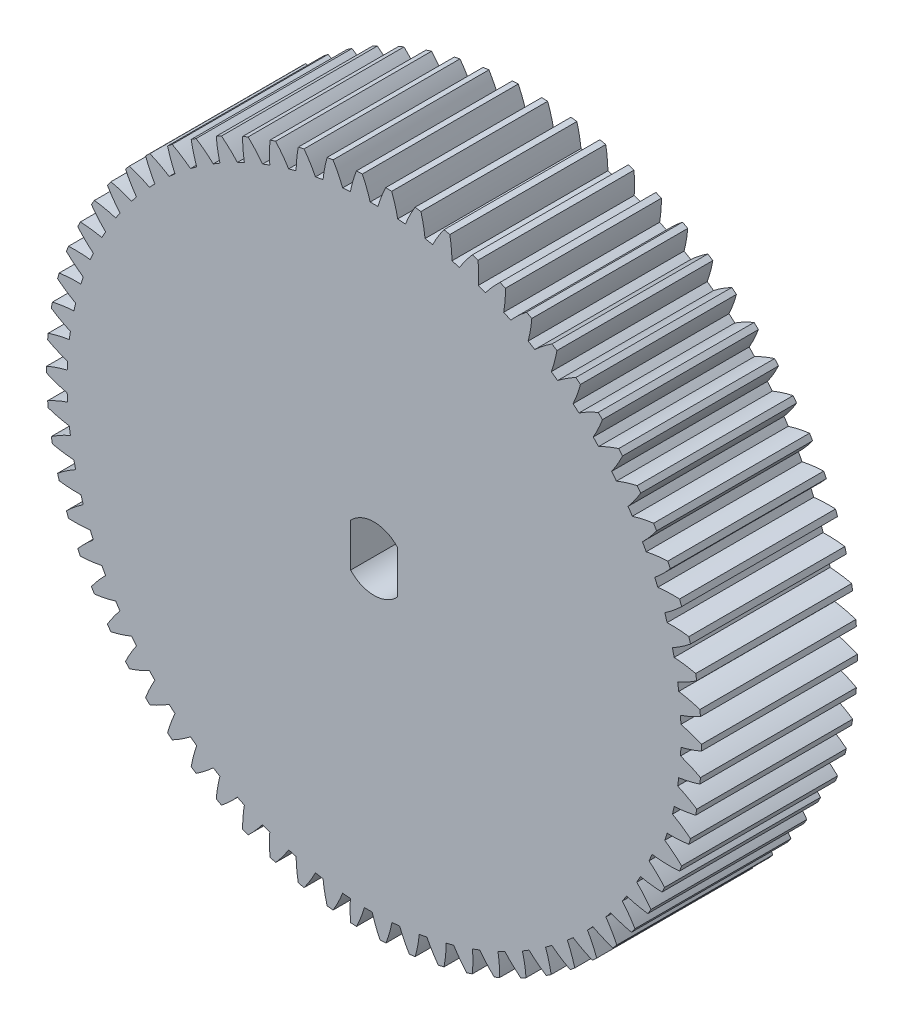
SolidWorks part; units mm, degrees
material "ABS"
ref_plane "Alzado" through (0, 0, 0) normal (0, 0, 1) x (1, 0, 0)
ref_plane "Planta" through (0, 0, 0) normal (0, 1, 0) x (1, 0, 0)
ref_plane "Vista lateral" through (0, 0, 0) normal (1, 0, 0) x (0, 0, -1)
sketch "Croquis1" plane through (0, 0, 0) normal (0, 0, 1) x (1, 0, 0)
  line L0 (0, 0) -> (0, 2.45) construction
  line L1 (0, 0) -> (0, 2.45) construction
  line L2 (-1.8, 1.6621) -> (-1.8, -1.6621)
  line L3 (1.8, 1.6621) -> (1.8, -1.6621)
  arc A0 (-25.199, -0.2281) -> (-23.6117, -0.7622) centre (-21.2911, 8.7591) ccw
  arc A1 (-23.6117, -0.7622) -> (-23.585, -1.3574) centre (0, 0) ccw
  arc A2 (-23.585, -1.3574) -> (-25.118, -2.0316) centre (-20.4203, -10.6323) ccw
  arc A3 (-25.118, -2.0316) -> (-25.0771, -2.486) centre (0, 0) ccw
  arc A4 (-25.0771, -2.486) -> (-23.4483, -2.8757) centre (-21.9906, 6.8153) ccw
  arc A5 (-23.4483, -2.8757) -> (-23.3684, -3.4661) centre (0, 0) ccw
  arc A6 (-23.3684, -3.4661) -> (-24.8347, -4.275) centre (-19.385, -12.42) ccw
  arc A7 (-24.8347, -4.275) -> (-24.7533, -4.7239) centre (0, 0) ccw
  arc A8 (-24.7533, -4.7239) -> (-23.0961, -4.966) centre (-22.513, 4.8166) ccw
  arc A9 (-23.0961, -4.966) -> (-22.9636, -5.5468) centre (0, 0) ccw
  arc A10 (-22.9636, -5.5468) -> (-24.3515, -6.484) centre (-18.1936, -14.1076) ccw
  arc A11 (-24.3515, -6.484) -> (-24.2302, -6.9237) centre (0, 0) ccw
  arc A12 (-24.2302, -6.9237) -> (-22.558, -7.0163) centre (-22.8541, 2.7792) ccw
  arc A13 (-22.558, -7.0163) -> (-22.3739, -7.5829) centre (0, 0) ccw
  arc A14 (-22.3739, -7.5829) -> (-23.6723, -8.6407) centre (-16.8558, -15.6817) ccw
  arc A15 (-23.6723, -8.6407) -> (-23.512, -9.0678) centre (0, 0) ccw
  arc A16 (-23.512, -9.0678) -> (-21.8383, -9.0102) centre (-23.0112, 0.7194) ccw
  arc A17 (-21.8383, -9.0102) -> (-21.6041, -9.558) centre (0, 0) ccw
  arc A18 (-21.6041, -9.558) -> (-22.8024, -10.7279) centre (-15.3822, -17.1295) ccw
  arc A19 (-22.8024, -10.7279) -> (-22.6045, -11.1389) centre (0, 0) ccw
  arc A20 (-22.6045, -11.1389) -> (-20.9427, -10.9315) centre (-22.9831, -1.3462) ccw
  arc A21 (-20.9427, -10.9315) -> (-20.6604, -11.4561) centre (0, 0) ccw
  arc A22 (-20.6604, -11.4561) -> (-21.749, -12.7287) centre (-13.7848, -18.4394) ccw
  arc A23 (-21.749, -12.7287) -> (-21.515, -13.1203) centre (0, 0) ccw
  arc A24 (-21.515, -13.1203) -> (-19.8785, -12.7648) centre (-22.7699, -3.401) ccw
  arc A25 (-19.8785, -12.7648) -> (-19.5503, -13.262) centre (0, 0) ccw
  arc A26 (-19.5503, -13.262) -> (-20.5205, -14.6271) centre (-12.0764, -19.6009) ccw
  arc A27 (-20.5205, -14.6271) -> (-20.2523, -14.9961) centre (0, 0) ccw
  arc A28 (-20.2523, -14.9961) -> (-18.6542, -14.4953) centre (-22.3733, -5.4284) ccw
  arc A29 (-18.6542, -14.4953) -> (-18.2828, -14.961) centre (0, 0) ccw
  arc A30 (-18.2828, -14.961) -> (-19.1267, -16.4076) centre (-10.2708, -20.6045) ccw
  arc A31 (-19.1267, -16.4076) -> (-18.8266, -16.7511) centre (0, 0) ccw
  arc A32 (-18.8266, -16.7511) -> (-17.2798, -16.1091) centre (-21.7967, -7.4121) ccw
  arc A33 (-17.2798, -16.1091) -> (-16.8681, -16.5397) centre (0, 0) ccw
  arc A34 (-16.8681, -16.5397) -> (-17.5789, -18.0561) centre (-8.3825, -21.4422) ccw
  arc A35 (-17.5789, -18.0561) -> (-17.2492, -18.3713) centre (0, 0) ccw
  arc A36 (-17.2492, -18.3713) -> (-15.7662, -17.5932) centre (-21.0445, -9.3361) ccw
  arc A37 (-15.7662, -17.5932) -> (-15.3176, -17.9851) centre (0, 0) ccw
  arc A38 (-15.3176, -17.9851) -> (-15.8896, -19.5591) centre (-6.4267, -22.1073) ccw
  arc A39 (-15.8896, -19.5591) -> (-15.533, -19.8436) centre (0, 0) ccw
  arc A40 (-15.533, -19.8436) -> (-14.1257, -18.9356) centre (-20.1229, -11.1849) ccw
  arc A41 (-14.1257, -18.9356) -> (-13.6437, -19.2858) centre (0, 0) ccw
  arc A42 (-13.6437, -19.2858) -> (-14.0724, -20.9047) centre (-4.4191, -22.5944) ccw
  arc A43 (-14.0724, -20.9047) -> (-13.6917, -21.156) centre (0, 0) ccw
  arc A44 (-13.6917, -21.156) -> (-12.3715, -20.1256) centre (-19.0393, -12.9437) ccw
  arc A45 (-12.3715, -20.1256) -> (-11.8601, -20.4312) centre (0, 0) ccw
  arc A46 (-11.8601, -20.4312) -> (-12.1419, -22.082) centre (-2.376, -22.8995) ccw
  arc A47 (-12.1419, -22.082) -> (-11.7401, -22.2982) centre (0, 0) ccw
  arc A48 (-11.7401, -22.2982) -> (-10.5176, -21.1536) centre (-17.8024, -14.5982) ccw
  arc A49 (-10.5176, -21.1536) -> (-9.9809, -21.412) centre (0, 0) ccw
  arc A50 (-9.9809, -21.412) -> (-10.1136, -23.0815) centre (-0.3137, -23.0203) ccw
  arc A51 (-10.1136, -23.0815) -> (-9.6941, -23.2608) centre (0, 0) ccw
  arc A52 (-9.6941, -23.2608) -> (-8.5791, -22.0112) centre (-16.4222, -16.1353) ccw
  arc A53 (-8.5791, -22.0112) -> (-8.0213, -22.2205) centre (0, 0) ccw
  arc A54 (-8.0213, -22.2205) -> (-8.0038, -23.8952) centre (1.751, -22.9558) ccw
  arc A55 (-8.0038, -23.8952) -> (-7.57, -24.0361) centre (0, 0) ccw
  arc A56 (-7.57, -24.0361) -> (-6.5715, -22.6916) centre (-14.9097, -17.5424) ccw
  arc A57 (-6.5715, -22.6916) -> (-5.9972, -22.8501) centre (0, 0) ccw
  arc A58 (-5.9972, -22.8501) -> (-5.8297, -24.5164) centre (3.8017, -22.7064) ccw
  arc A59 (-5.8297, -24.5164) -> (-5.3849, -24.6179) centre (0, 0) ccw
  arc A60 (-5.3849, -24.6179) -> (-4.511, -23.1893) centre (-13.2772, -18.8083) ccw
  arc A61 (-4.511, -23.1893) -> (-3.9248, -23.2957) centre (0, 0) ccw
  arc A62 (-3.9248, -23.2957) -> (-3.6086, -24.9403) centre (5.8218, -22.2742) ccw
  arc A63 (-3.6086, -24.9403) -> (-3.1565, -25.0015) centre (0, 0) ccw
  arc A64 (-3.1565, -25.0015) -> (-2.4141, -23.5003) centre (-11.5378, -19.9227) ccw
  arc A65 (-2.4141, -23.5003) -> (-1.8208, -23.5537) centre (0, 0) ccw
  arc A66 (-1.8208, -23.5537) -> (-1.8, -25.1634) centre (7.9557, -24.2324) ccw
  arc A67 (-1.8, -25.1634) -> (-1.3443, -25.1838) centre (-0.4416, 0) ccw
  arc A68 (-1.3443, -25.1838) -> (-0.7395, -23.6221) centre (-10.1471, -20.8767) ccw
  arc A69 (-0.7395, -23.6221) -> (-0.1437, -23.6221) centre (-0.4416, 0) ccw
  arc A70 (-0.1437, -23.6221) -> (0.4611, -25.1838) centre (9.2639, -20.8767) ccw
  arc A71 (0.4611, -25.1838) -> (0.9168, -25.1634) centre (-0.4416, 0) ccw
  arc A72 (0.9168, -25.1634) -> (1.3792, -23.5537) centre (-8.2366, -21.6627) ccw
  arc A73 (1.3792, -23.5537) -> (1.9726, -23.5003) centre (-0.4416, 0) ccw
  arc A74 (1.9726, -23.5003) -> (2.7149, -25.0015) centre (11.0962, -19.9227) ccw
  arc A75 (2.7149, -25.0015) -> (3.167, -24.9403) centre (-0.4416, 0) ccw
  arc A76 (3.167, -24.9403) -> (3.4832, -23.2957) centre (-6.2634, -22.2742) ccw
  arc A77 (3.4832, -23.2957) -> (4.0694, -23.1893) centre (-0.4416, 0) ccw
  arc A78 (4.0694, -23.1893) -> (4.9433, -24.6179) centre (12.8356, -18.8083) ccw
  arc A79 (4.9433, -24.6179) -> (5.3881, -24.5164) centre (-0.4416, 0) ccw
  arc A80 (5.3881, -24.5164) -> (5.5556, -22.8501) centre (-4.2433, -22.7064) ccw
  arc A81 (5.5556, -22.8501) -> (6.1299, -22.6916) centre (-0.4416, 0) ccw
  arc A82 (6.1299, -22.6916) -> (7.1284, -24.0361) centre (14.4681, -17.5424) ccw
  arc A83 (7.1284, -24.0361) -> (7.5622, -23.8952) centre (-0.4416, 0) ccw
  arc A84 (7.5622, -23.8952) -> (7.5797, -22.2205) centre (-2.1926, -22.9558) ccw
  arc A85 (7.5797, -22.2205) -> (8.1375, -22.0112) centre (-0.4416, 0) ccw
  arc A86 (8.1375, -22.0112) -> (9.2525, -23.2608) centre (15.9806, -16.1353) ccw
  arc A87 (9.2525, -23.2608) -> (9.672, -23.0815) centre (-0.4416, 0) ccw
  arc A88 (9.672, -23.0815) -> (9.5393, -21.412) centre (-0.1278, -23.0203) ccw
  arc A89 (9.5393, -21.412) -> (10.076, -21.1536) centre (-0.4416, 0) ccw
  arc A90 (10.076, -21.1536) -> (11.2986, -22.2982) centre (17.3608, -14.5982) ccw
  arc A91 (11.2986, -22.2982) -> (11.7003, -22.082) centre (-0.4416, 0) ccw
  arc A92 (11.7003, -22.082) -> (11.4185, -20.4312) centre (1.9344, -22.8995) ccw
  arc A93 (11.4185, -20.4312) -> (11.9299, -20.1256) centre (-0.4416, 0) ccw
  arc A94 (11.9299, -20.1256) -> (13.2501, -21.156) centre (18.5977, -12.9437) ccw
  arc A95 (13.2501, -21.156) -> (13.6308, -20.9047) centre (-0.4416, 0) ccw
  arc A96 (13.6308, -20.9047) -> (13.2022, -19.2858) centre (3.9775, -22.5944) ccw
  arc A97 (13.2022, -19.2858) -> (13.6841, -18.9356) centre (-0.4416, 0) ccw
  arc A98 (13.6841, -18.9356) -> (15.0914, -19.8436) centre (19.6813, -11.1849) ccw
  arc A99 (15.0914, -19.8436) -> (15.448, -19.5591) centre (-0.4416, 0) ccw
  arc A100 (15.448, -19.5591) -> (14.876, -17.9851) centre (5.9851, -22.1073) ccw
  arc A101 (14.876, -17.9851) -> (15.3246, -17.5932) centre (-0.4416, 0) ccw
  arc A102 (15.3246, -17.5932) -> (16.8076, -18.3713) centre (20.6029, -9.3361) ccw
  arc A103 (16.8076, -18.3713) -> (17.1373, -18.0561) centre (-0.4416, 0) ccw
  arc A104 (17.1373, -18.0561) -> (16.4265, -16.5397) centre (7.9409, -21.4422) ccw
  arc A105 (16.4265, -16.5397) -> (16.8382, -16.1091) centre (-0.4416, 0) ccw
  arc A106 (16.8382, -16.1091) -> (18.385, -16.7511) centre (21.3551, -7.4121) ccw
  arc A107 (18.385, -16.7511) -> (18.6851, -16.4076) centre (-0.4416, 0) ccw
  arc A108 (18.6851, -16.4076) -> (17.8412, -14.961) centre (9.8292, -20.6045) ccw
  arc A109 (17.8412, -14.961) -> (18.2126, -14.4953) centre (-0.4416, 0) ccw
  arc A110 (18.2126, -14.4953) -> (19.8107, -14.9961) centre (21.9318, -5.4284) ccw
  arc A111 (19.8107, -14.9961) -> (20.0789, -14.6271) centre (-0.4416, 0) ccw
  arc A112 (20.0789, -14.6271) -> (19.1087, -13.262) centre (11.6349, -19.6009) ccw
  arc A113 (19.1087, -13.262) -> (19.4369, -12.7648) centre (-0.4416, 0) ccw
  arc A114 (19.4369, -12.7648) -> (21.0734, -13.1203) centre (22.3283, -3.401) ccw
  arc A115 (21.0734, -13.1203) -> (21.3074, -12.7287) centre (-0.4416, 0) ccw
  arc A116 (21.3074, -12.7287) -> (20.2188, -11.4561) centre (13.3432, -18.4394) ccw
  arc A117 (20.2188, -11.4561) -> (20.5011, -10.9315) centre (-0.4416, 0) ccw
  arc A118 (20.5011, -10.9315) -> (22.1629, -11.1389) centre (22.5415, -1.3462) ccw
  arc A119 (22.1629, -11.1389) -> (22.3609, -10.7279) centre (-0.4416, 0) ccw
  arc A120 (22.3609, -10.7279) -> (21.1625, -9.558) centre (14.9406, -17.1295) ccw
  arc A121 (21.1625, -9.558) -> (21.3967, -9.0102) centre (-0.4416, 0) ccw
  arc A122 (21.3967, -9.0102) -> (23.512, -9.0678) centre (22.7197, 0.7001) ccw
  arc A123 (23.512, -9.0678) -> (23.6723, -8.6407) centre (0, 0) ccw
  arc A124 (23.6723, -8.6407) -> (22.3739, -7.5829) centre (16.8558, -15.6817) ccw
  arc A125 (22.3739, -7.5829) -> (22.558, -7.0163) centre (0, 0) ccw
  arc A126 (22.558, -7.0163) -> (24.2302, -6.9237) centre (22.8541, 2.7792) ccw
  arc A127 (24.2302, -6.9237) -> (24.3515, -6.484) centre (0, 0) ccw
  arc A128 (24.3515, -6.484) -> (22.9636, -5.5468) centre (18.1936, -14.1076) ccw
  arc A129 (22.9636, -5.5468) -> (23.0961, -4.966) centre (0, 0) ccw
  arc A130 (23.0961, -4.966) -> (24.7533, -4.7239) centre (22.513, 4.8166) ccw
  arc A131 (24.7533, -4.7239) -> (24.8347, -4.275) centre (0, 0) ccw
  arc A132 (24.8347, -4.275) -> (23.3684, -3.4661) centre (19.385, -12.42) ccw
  arc A133 (23.3684, -3.4661) -> (23.4483, -2.8757) centre (0, 0) ccw
  arc A134 (23.4483, -2.8757) -> (25.0771, -2.486) centre (21.9906, 6.8153) ccw
  arc A135 (25.0771, -2.486) -> (25.118, -2.0316) centre (0, 0) ccw
  arc A136 (25.118, -2.0316) -> (23.585, -1.3574) centre (20.4203, -10.6323) ccw
  arc A137 (23.585, -1.3574) -> (23.6117, -0.7622) centre (0, 0) ccw
  arc A138 (23.6117, -0.7622) -> (25.199, -0.2281) centre (21.2911, 8.7591) ccw
  arc A139 (25.199, -0.2281) -> (25.199, 0.2281) centre (0, 0) ccw
  arc A140 (25.199, 0.2281) -> (23.6117, 0.7622) centre (21.2911, -8.7591) ccw
  arc A141 (23.6117, 0.7622) -> (23.585, 1.3574) centre (0, 0) ccw
  arc A142 (23.585, 1.3574) -> (25.118, 2.0316) centre (20.4203, 10.6323) ccw
  arc A143 (25.118, 2.0316) -> (25.0771, 2.486) centre (0, 0) ccw
  arc A144 (25.0771, 2.486) -> (23.4483, 2.8757) centre (21.9906, -6.8153) ccw
  arc A145 (23.4483, 2.8757) -> (23.3684, 3.4661) centre (0, 0) ccw
  arc A146 (23.3684, 3.4661) -> (24.8347, 4.275) centre (19.385, 12.42) ccw
  arc A147 (24.8347, 4.275) -> (24.7533, 4.7239) centre (0, 0) ccw
  arc A148 (24.7533, 4.7239) -> (23.0961, 4.966) centre (22.513, -4.8166) ccw
  arc A149 (23.0961, 4.966) -> (22.9636, 5.5468) centre (0, 0) ccw
  arc A150 (22.9636, 5.5468) -> (24.3515, 6.484) centre (18.1936, 14.1076) ccw
  arc A151 (24.3515, 6.484) -> (24.2302, 6.9237) centre (0, 0) ccw
  arc A152 (24.2302, 6.9237) -> (22.558, 7.0163) centre (22.8541, -2.7792) ccw
  arc A153 (22.558, 7.0163) -> (22.3739, 7.5829) centre (0, 0) ccw
  arc A154 (22.3739, 7.5829) -> (23.6723, 8.6407) centre (16.8558, 15.6817) ccw
  arc A155 (23.6723, 8.6407) -> (23.512, 9.0678) centre (0, 0) ccw
  arc A156 (23.512, 9.0678) -> (21.8383, 9.0102) centre (23.0112, -0.7194) ccw
  arc A157 (21.8383, 9.0102) -> (21.6041, 9.558) centre (0, 0) ccw
  arc A158 (21.6041, 9.558) -> (22.8024, 10.7279) centre (15.3822, 17.1295) ccw
  arc A159 (22.8024, 10.7279) -> (22.6045, 11.1389) centre (0, 0) ccw
  arc A160 (22.6045, 11.1389) -> (20.9427, 10.9315) centre (22.9831, 1.3462) ccw
  arc A161 (20.9427, 10.9315) -> (20.6604, 11.4561) centre (0, 0) ccw
  arc A162 (20.6604, 11.4561) -> (21.749, 12.7287) centre (13.7848, 18.4394) ccw
  arc A163 (21.749, 12.7287) -> (21.515, 13.1203) centre (0, 0) ccw
  arc A164 (21.515, 13.1203) -> (19.8785, 12.7648) centre (22.7699, 3.401) ccw
  arc A165 (19.8785, 12.7648) -> (19.5503, 13.262) centre (0, 0) ccw
  arc A166 (19.5503, 13.262) -> (20.5205, 14.6271) centre (12.0764, 19.6009) ccw
  arc A167 (20.5205, 14.6271) -> (20.2523, 14.9961) centre (0, 0) ccw
  arc A168 (20.2523, 14.9961) -> (18.6542, 14.4953) centre (22.3733, 5.4284) ccw
  arc A169 (18.6542, 14.4953) -> (18.2828, 14.961) centre (0, 0) ccw
  arc A170 (18.2828, 14.961) -> (19.1267, 16.4076) centre (10.2708, 20.6045) ccw
  arc A171 (19.1267, 16.4076) -> (18.8266, 16.7511) centre (0, 0) ccw
  arc A172 (18.8266, 16.7511) -> (17.2798, 16.1091) centre (21.7967, 7.4121) ccw
  arc A173 (17.2798, 16.1091) -> (16.8681, 16.5397) centre (0, 0) ccw
  arc A174 (16.8681, 16.5397) -> (17.5789, 18.0561) centre (8.3825, 21.4422) ccw
  arc A175 (17.5789, 18.0561) -> (17.2492, 18.3713) centre (0, 0) ccw
  arc A176 (17.2492, 18.3713) -> (15.7662, 17.5932) centre (21.0445, 9.3361) ccw
  arc A177 (15.7662, 17.5932) -> (15.3176, 17.9851) centre (0, 0) ccw
  arc A178 (15.3176, 17.9851) -> (15.8896, 19.5591) centre (6.4267, 22.1073) ccw
  arc A179 (15.8896, 19.5591) -> (15.533, 19.8436) centre (0, 0) ccw
  arc A180 (15.533, 19.8436) -> (14.1257, 18.9356) centre (20.1229, 11.1849) ccw
  arc A181 (14.1257, 18.9356) -> (13.6437, 19.2858) centre (0, 0) ccw
  arc A182 (13.6437, 19.2858) -> (14.0724, 20.9047) centre (4.4191, 22.5944) ccw
  arc A183 (14.0724, 20.9047) -> (13.6917, 21.156) centre (0, 0) ccw
  arc A184 (13.6917, 21.156) -> (12.3715, 20.1256) centre (19.0393, 12.9437) ccw
  arc A185 (12.3715, 20.1256) -> (11.8601, 20.4312) centre (0, 0) ccw
  arc A186 (11.8601, 20.4312) -> (12.1419, 22.082) centre (2.376, 22.8995) ccw
  arc A187 (12.1419, 22.082) -> (11.7401, 22.2982) centre (0, 0) ccw
  arc A188 (11.7401, 22.2982) -> (10.5176, 21.1536) centre (17.8024, 14.5982) ccw
  arc A189 (10.5176, 21.1536) -> (9.9809, 21.412) centre (0, 0) ccw
  arc A190 (9.9809, 21.412) -> (10.1136, 23.0815) centre (0.3137, 23.0203) ccw
  arc A191 (10.1136, 23.0815) -> (9.6941, 23.2608) centre (0, 0) ccw
  arc A192 (9.6941, 23.2608) -> (8.5791, 22.0112) centre (16.4222, 16.1353) ccw
  arc A193 (8.5791, 22.0112) -> (8.0213, 22.2205) centre (0, 0) ccw
  arc A194 (8.0213, 22.2205) -> (8.0038, 23.8952) centre (-1.751, 22.9558) ccw
  arc A195 (8.0038, 23.8952) -> (7.57, 24.0361) centre (0, 0) ccw
  arc A196 (7.57, 24.0361) -> (6.5715, 22.6916) centre (14.9097, 17.5424) ccw
  arc A197 (6.5715, 22.6916) -> (5.9972, 22.8501) centre (0, 0) ccw
  arc A198 (5.9972, 22.8501) -> (5.8297, 24.5164) centre (-3.8017, 22.7064) ccw
  arc A199 (5.8297, 24.5164) -> (5.3849, 24.6179) centre (0, 0) ccw
  arc A200 (5.3849, 24.6179) -> (4.511, 23.1893) centre (13.2772, 18.8083) ccw
  arc A201 (4.511, 23.1893) -> (3.9248, 23.2957) centre (0, 0) ccw
  arc A202 (3.9248, 23.2957) -> (3.6086, 24.9403) centre (-5.8218, 22.2742) ccw
  arc A203 (3.6086, 24.9403) -> (3.1565, 25.0015) centre (0, 0) ccw
  arc A204 (3.1565, 25.0015) -> (2.4141, 23.5003) centre (11.5378, 19.9227) ccw
  arc A205 (2.4141, 23.5003) -> (1.8208, 23.5537) centre (0, 0) ccw
  arc A206 (1.8208, 23.5537) -> (1.3584, 25.1634) centre (-7.795, 21.6627) ccw
  arc A207 (1.3584, 25.1634) -> (0.9027, 25.1838) centre (0, 0) ccw
  arc A208 (0.9027, 25.1838) -> (0.2979, 23.6221) centre (9.7055, 20.8767) ccw
  arc A209 (0.2979, 23.6221) -> (-0.2979, 23.6221) centre (0, 0) ccw
  arc A210 (-0.2979, 23.6221) -> (-0.9027, 25.1838) centre (-9.7055, 20.8767) ccw
  arc A211 (-0.9027, 25.1838) -> (-1.3584, 25.1634) centre (0, 0) ccw
  arc A212 (-1.3584, 25.1634) -> (-1.8208, 23.5537) centre (7.795, 21.6627) ccw
  arc A213 (-1.8208, 23.5537) -> (-2.4141, 23.5003) centre (0, 0) ccw
  arc A214 (-2.4141, 23.5003) -> (-3.1565, 25.0015) centre (-11.5378, 19.9227) ccw
  arc A215 (-3.1565, 25.0015) -> (-3.6086, 24.9403) centre (0, 0) ccw
  arc A216 (-3.6086, 24.9403) -> (-3.9248, 23.2957) centre (5.8218, 22.2742) ccw
  arc A217 (-3.9248, 23.2957) -> (-4.511, 23.1893) centre (0, 0) ccw
  arc A218 (-4.511, 23.1893) -> (-5.3849, 24.6179) centre (-13.2772, 18.8083) ccw
  arc A219 (-5.3849, 24.6179) -> (-5.8297, 24.5164) centre (0, 0) ccw
  arc A220 (-5.8297, 24.5164) -> (-5.9972, 22.8501) centre (3.8017, 22.7064) ccw
  arc A221 (-5.9972, 22.8501) -> (-6.5715, 22.6916) centre (0, 0) ccw
  arc A222 (-6.5715, 22.6916) -> (-7.57, 24.0361) centre (-14.9097, 17.5424) ccw
  arc A223 (-7.57, 24.0361) -> (-8.0038, 23.8952) centre (0, 0) ccw
  arc A224 (-8.0038, 23.8952) -> (-8.0213, 22.2205) centre (1.751, 22.9558) ccw
  arc A225 (-8.0213, 22.2205) -> (-8.5791, 22.0112) centre (0, 0) ccw
  arc A226 (-8.5791, 22.0112) -> (-9.6941, 23.2608) centre (-16.4222, 16.1353) ccw
  arc A227 (-9.6941, 23.2608) -> (-10.1136, 23.0815) centre (0, 0) ccw
  arc A228 (-10.1136, 23.0815) -> (-9.9809, 21.412) centre (-0.3137, 23.0203) ccw
  arc A229 (-9.9809, 21.412) -> (-10.5176, 21.1536) centre (0, 0) ccw
  arc A230 (-10.5176, 21.1536) -> (-11.7401, 22.2982) centre (-17.8024, 14.5982) ccw
  arc A231 (-11.7401, 22.2982) -> (-12.1419, 22.082) centre (0, 0) ccw
  arc A232 (-12.1419, 22.082) -> (-11.8601, 20.4312) centre (-2.376, 22.8995) ccw
  arc A233 (-11.8601, 20.4312) -> (-12.3715, 20.1256) centre (0, 0) ccw
  arc A234 (-12.3715, 20.1256) -> (-13.6917, 21.156) centre (-19.0393, 12.9437) ccw
  arc A235 (-13.6917, 21.156) -> (-14.0724, 20.9047) centre (0, 0) ccw
  arc A236 (-14.0724, 20.9047) -> (-13.6437, 19.2858) centre (-4.4191, 22.5944) ccw
  arc A237 (-13.6437, 19.2858) -> (-14.1257, 18.9356) centre (0, 0) ccw
  arc A238 (-14.1257, 18.9356) -> (-15.533, 19.8436) centre (-20.1229, 11.1849) ccw
  arc A239 (-15.533, 19.8436) -> (-15.8896, 19.5591) centre (0, 0) ccw
  arc A240 (-15.8896, 19.5591) -> (-15.3176, 17.9851) centre (-6.4267, 22.1073) ccw
  arc A241 (-15.3176, 17.9851) -> (-15.7662, 17.5932) centre (0, 0) ccw
  arc A242 (-15.7662, 17.5932) -> (-17.2492, 18.3713) centre (-21.0445, 9.3361) ccw
  arc A243 (-17.2492, 18.3713) -> (-17.5789, 18.0561) centre (0, 0) ccw
  arc A244 (-17.5789, 18.0561) -> (-16.8681, 16.5397) centre (-8.3825, 21.4422) ccw
  arc A245 (-16.8681, 16.5397) -> (-17.2798, 16.1091) centre (0, 0) ccw
  arc A246 (-17.2798, 16.1091) -> (-18.8266, 16.7511) centre (-21.7967, 7.4121) ccw
  arc A247 (-18.8266, 16.7511) -> (-19.1267, 16.4076) centre (0, 0) ccw
  arc A248 (-19.1267, 16.4076) -> (-18.2828, 14.961) centre (-10.2708, 20.6045) ccw
  arc A249 (-18.2828, 14.961) -> (-18.6542, 14.4953) centre (0, 0) ccw
  arc A250 (-18.6542, 14.4953) -> (-20.2523, 14.9961) centre (-22.3733, 5.4284) ccw
  arc A251 (-20.2523, 14.9961) -> (-20.5205, 14.6271) centre (0, 0) ccw
  arc A252 (-20.5205, 14.6271) -> (-19.5503, 13.262) centre (-12.0764, 19.6009) ccw
  arc A253 (-19.5503, 13.262) -> (-19.8785, 12.7648) centre (0, 0) ccw
  arc A254 (-19.8785, 12.7648) -> (-21.515, 13.1203) centre (-22.7699, 3.401) ccw
  arc A255 (-21.515, 13.1203) -> (-21.749, 12.7287) centre (0, 0) ccw
  arc A256 (-21.749, 12.7287) -> (-20.6604, 11.4561) centre (-13.7848, 18.4394) ccw
  arc A257 (-20.6604, 11.4561) -> (-20.9427, 10.9315) centre (0, 0) ccw
  arc A258 (-20.9427, 10.9315) -> (-22.6045, 11.1389) centre (-22.9831, 1.3462) ccw
  arc A259 (-22.6045, 11.1389) -> (-22.8024, 10.7279) centre (0, 0) ccw
  arc A260 (-22.8024, 10.7279) -> (-21.6041, 9.558) centre (-15.3822, 17.1295) ccw
  arc A261 (-21.6041, 9.558) -> (-21.8383, 9.0102) centre (0, 0) ccw
  arc A262 (-21.8383, 9.0102) -> (-23.512, 9.0678) centre (-23.0112, -0.7194) ccw
  arc A263 (-23.512, 9.0678) -> (-23.6723, 8.6407) centre (0, 0) ccw
  arc A264 (-23.6723, 8.6407) -> (-22.3739, 7.5829) centre (-16.8558, 15.6817) ccw
  arc A265 (-22.3739, 7.5829) -> (-22.558, 7.0163) centre (0, 0) ccw
  arc A266 (-22.558, 7.0163) -> (-24.2302, 6.9237) centre (-22.8541, -2.7792) ccw
  arc A267 (-24.2302, 6.9237) -> (-24.3515, 6.484) centre (0, 0) ccw
  arc A268 (-24.3515, 6.484) -> (-22.9636, 5.5468) centre (-18.1936, 14.1076) ccw
  arc A269 (-22.9636, 5.5468) -> (-23.0961, 4.966) centre (0, 0) ccw
  arc A270 (-23.0961, 4.966) -> (-24.7533, 4.7239) centre (-22.513, -4.8166) ccw
  arc A271 (-24.7533, 4.7239) -> (-24.8347, 4.275) centre (0, 0) ccw
  arc A272 (-24.8347, 4.275) -> (-23.3684, 3.4661) centre (-19.385, 12.42) ccw
  arc A273 (-23.3684, 3.4661) -> (-23.4483, 2.8757) centre (0, 0) ccw
  arc A274 (-23.4483, 2.8757) -> (-25.0771, 2.486) centre (-21.9906, -6.8153) ccw
  arc A275 (-25.0771, 2.486) -> (-25.118, 2.0316) centre (0, 0) ccw
  arc A276 (-25.118, 2.0316) -> (-23.585, 1.3574) centre (-20.4203, 10.6323) ccw
  arc A277 (-23.585, 1.3574) -> (-23.6117, 0.7622) centre (0, 0) ccw
  arc A278 (-23.6117, 0.7622) -> (-25.199, 0.2281) centre (-21.2911, -8.7591) ccw
  arc A279 (-25.199, 0.2281) -> (-25.199, -0.2281) centre (0, 0) ccw
  arc A280 (-1.8, -1.6621) -> (1.8, -1.6621) centre (0, 0) ccw
  arc A281 (1.8, 1.6621) -> (-1.8, 1.6621) centre (0, 0) ccw
  dimension "D1" = 23.624
  dimension "D2" = 25.2
  dimension "D3" = 4.9
  dimension "D4" = 3.6
extrude "Saliente-Extruir1" add sketch "Croquis1" along normal blind 12
sketch "Croquis2" plane through (0, 0, 12) normal (0, 0, 1) x (1, 0, 0)
  circle A0 centre (0, 0) radius 23.624
